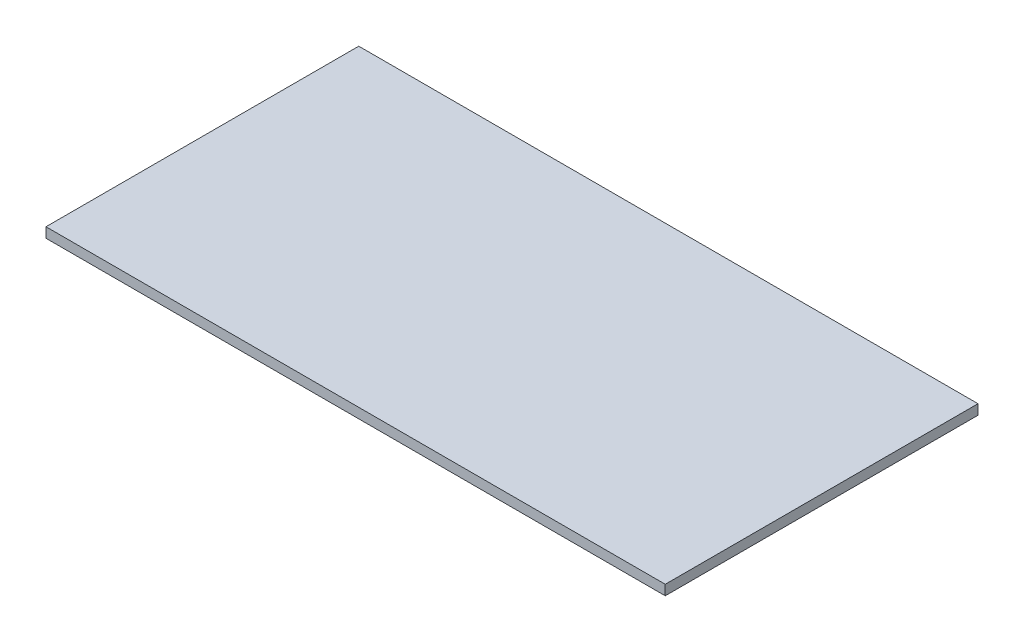
SolidWorks part; units mm, degrees
material "Custom Plastic"
ref_plane "Front Plane" through (0, 0, 0) normal (0, 0, 1) x (1, 0, 0)
ref_plane "Top Plane" through (0, 0, 0) normal (0, 1, 0) x (1, 0, 0)
ref_plane "Right Plane" through (0, 0, 0) normal (1, 0, 0) x (0, 0, -1)
sketch "Sketch1" plane through (0, 0, 0) normal (0, 1, 0) x (1, 0, 0)
  line L1 (-53.0588, 16.9853) -> (45.9412, 16.9853)
  line L2 (-53.0588, 16.9853) -> (-53.0588, -33.0147)
  line L3 (-53.0588, -33.0147) -> (45.9412, -33.0147)
  line L4 (45.9412, 16.9853) -> (45.9412, -33.0147)
  dimension "D1" = 99
  dimension "D2" = 50
extrude "Boss-Extrude1" add sketch "Sketch1" along normal blind 1.6
